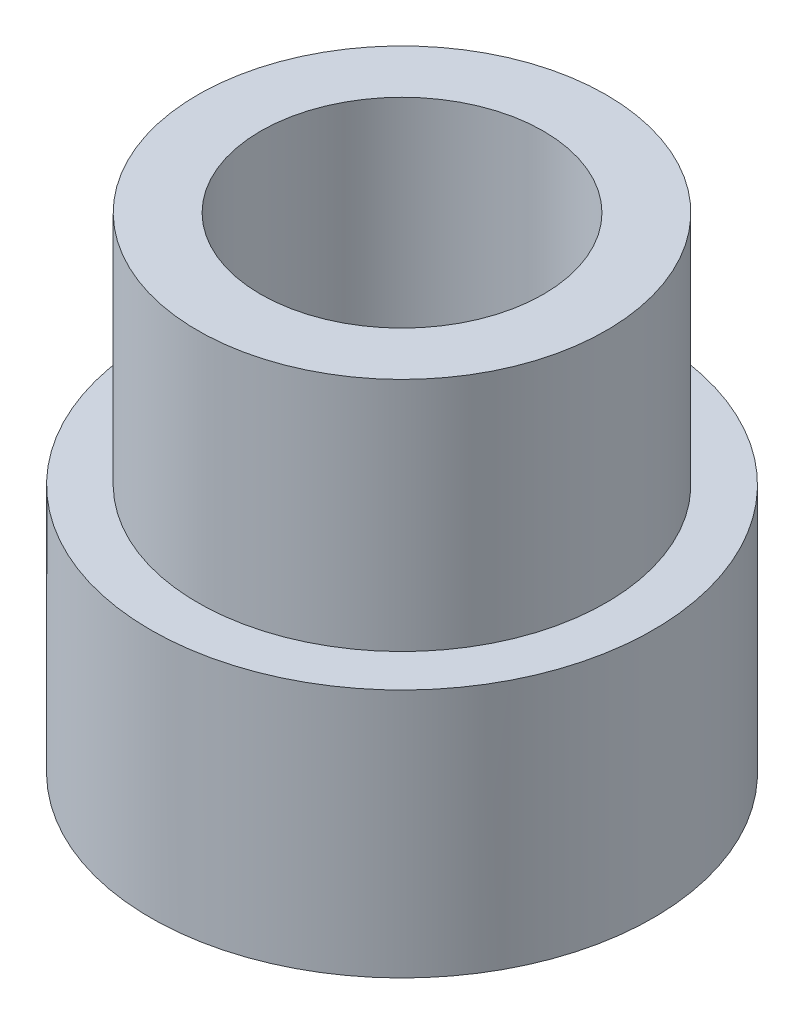
SolidWorks part; units mm, degrees
ref_plane "Front Plane" through (0, 0, 0) normal (0, 0, 1) x (1, 0, 0)
ref_plane "Top Plane" through (0, 0, 0) normal (0, 1, 0) x (1, 0, 0)
ref_plane "Right Plane" through (0, 0, 0) normal (1, 0, 0) x (0, 0, -1)
sketch "Sketch1" plane through (0, 0, 0) normal (0, 1, 0) x (1, 0, 0)
  circle A0 centre (0, 0) radius 20.32
  circle A1 centre (0, 0) radius 4.6355
  dimension "D1" = 40.64
  dimension "D2" = 9.271
extrude "Boss-Extrude1" add sketch "Sketch1" along normal blind 10
sketch "Sketch2" plane through (0, 10, 0) normal (0, 1, 0) x (1, 0, 0)
  circle A0 centre (0, 0) radius 16.51
  circle A1 centre (0, 0) radius 11.43
  dimension "D1" = 33.02
  dimension "D2" = 22.86
extrude "Boss-Extrude2" add sketch "Sketch2" along normal blind 19.05
sketch "Sketch3" plane through (0, 0, 0) normal (0, -1, 0) x (-1, 0, 0)
  circle A0 centre (0, 0) radius 20.32
  circle A1 centre (0, 0) radius 4.6355
  circle A2 centre (0, 0) radius 20.32 construction
  circle A3 centre (0, 0) radius 4.6355 construction
extrude "Boss-Extrude3" add sketch "Sketch3" along normal blind 10.16
sketch "Sketch4" plane through (0, 10, 0) normal (0, 1, 0) x (1, 0, 0)
  circle A0 centre (0, 0) radius 11.43
  circle A1 centre (0, 0) radius 11.43 construction
extrude "Cut-Extrude1" cut sketch "Sketch4" against normal blind 12
sketch "Sketch6" plane through (0, -10.16, 0) normal (0, -1, 0) x (1, 0, 0)
  circle A0 centre (0, 0) radius 11.25
  dimension "D1" = 22.5
extrude "Cut-Extrude3" cut sketch "Sketch6" against normal blind 6.5
sketch "Sketch7" plane through (0, -3.66, 0) normal (0, -1, 0) x (-1, 0, 0)
  circle A0 centre (0, 0) radius 8.5
  dimension "D1" = 17
extrude "Cut-Extrude4" cut sketch "Sketch7" against normal blind 0.75
